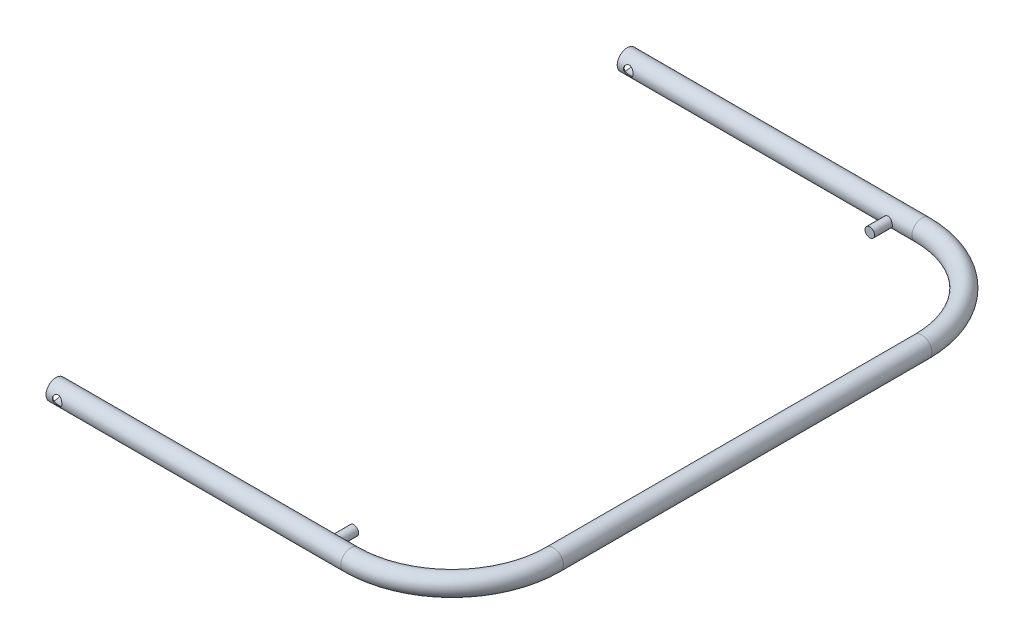
SolidWorks part; units mm, degrees
ref_plane "Front Plane" through (0, 0, 0) normal (0, 0, 1) x (1, 0, 0)
ref_plane "Top Plane" through (0, 0, 0) normal (0, 1, 0) x (1, 0, 0)
ref_plane "Right Plane" through (0, 0, 0) normal (1, 0, 0) x (0, 0, -1)
sketch "Sketch1" plane through (0, 0, 0) normal (0, 1, 0) x (1, 0, 0)
  line L0 (0, 400) -> (400, 400)
  line L1 (550, 250) -> (550, -250)
  line L2 (400, -400) -> (0, -400)
  line L3 (-768.8564, 0) -> (914.8418, 0) construction
  arc A0 (550, -250) -> (400, -400) centre (400, -250) cw
  arc A1 (400, 400) -> (550, 250) centre (400, 250) cw
  point P12 (550, -400)
  point P15 (550, 400)
  dimension "D3" = 150
  dimension "D1" = 800
  dimension "D2" = 550
ref_plane "Plane1" through (0, 0, -400) normal (1, 0, 0) x (0, 0, -1)
sketch "Sketch2" plane through (0, 0, -400) normal (1, 0, 0) x (0, 0, -1)
  line L0 (0, 0) -> (-150, 0) construction
  circle A0 centre (-12.5, 0) radius 12.5
  dimension "D1" = 25
sweep "Sweep-Thin1" add profiles "Sketch2" path "Sketch1" parameters "D1"=1
ref_plane "Plane2" through (0, 12.5, 0) normal (0, 1, 0) x (1, 0, 0)
sketch "Sketch10" plane through (0, 12.5, 0) normal (0, 1, 0) x (1, 0, 0)
  line L0 (45, 387.5) -> (45, -387.5)
  line L1 (45, -387.5) -> (400, -387.5)
  line L2 (400, -401) -> (400, -374) construction
  line L3 (400, -387.5) -> (537.5, -250)
  line L4 (524, -250) -> (551, -250) construction
  line L5 (537.5, -250) -> (537.5, 250)
  line L6 (551, 250) -> (524, 250) construction
  line L7 (537.5, 250) -> (400, 387.5)
  line L8 (400, 374) -> (400, 401) construction
  line L9 (400, 387.5) -> (45, 387.5)
  line L10 (0, -375) -> (0, -400) construction
  dimension "D1" = 45
sketch "Sketch11" plane through (0, 0, 0) normal (0, 0, 1) x (1, 0, 0)
  line L0 (0, 0) -> (400, 0) construction
  line L1 (400, 13.5) -> (400, -13.5) construction
  circle A0 centre (15, 0) radius 6.5
  dimension "D1" = 13
  dimension "D2" = 15
extrude "Cut-Extrude1" cut sketch "Sketch11" against normal mid plane 1033 contours A0
ref_plane "Plane3" through (0, 0, -350) normal (0, 0, 1) x (1, 0, 0)
sketch "Sketch12" plane through (0, 0, -350) normal (0, 0, 1) x (1, 0, 0)
  circle A0 centre (366.7311, -1.3177) radius 6.5
  dimension "D1" = 13
extrude "Boss-Extrude1" add sketch "Sketch12" against normal up to next
ref_plane "Plane4" through (0, 0, 350) normal (0, 0, 1) x (1, 0, 0)
sketch "Sketch13" plane through (0, 0, 350) normal (0, 0, 1) x (1, 0, 0)
  circle A1 centre (366.7311, -1.3177) radius 6.5
  circle A2 centre (366.7311, -1.3177) radius 6.5
  dimension "D1" = 0
extrude "Boss-Extrude2" add sketch "Sketch13" along normal up to next
sketch "Bend-Lines1" [suppressed] plane through (0, 0, 0) normal (0, 1, 0) x (1, 0, 0)
sketch "Bounding-Box1" [suppressed] plane through (0, 0, 0) normal (0, 1, 0) x (1, 0, 0)
